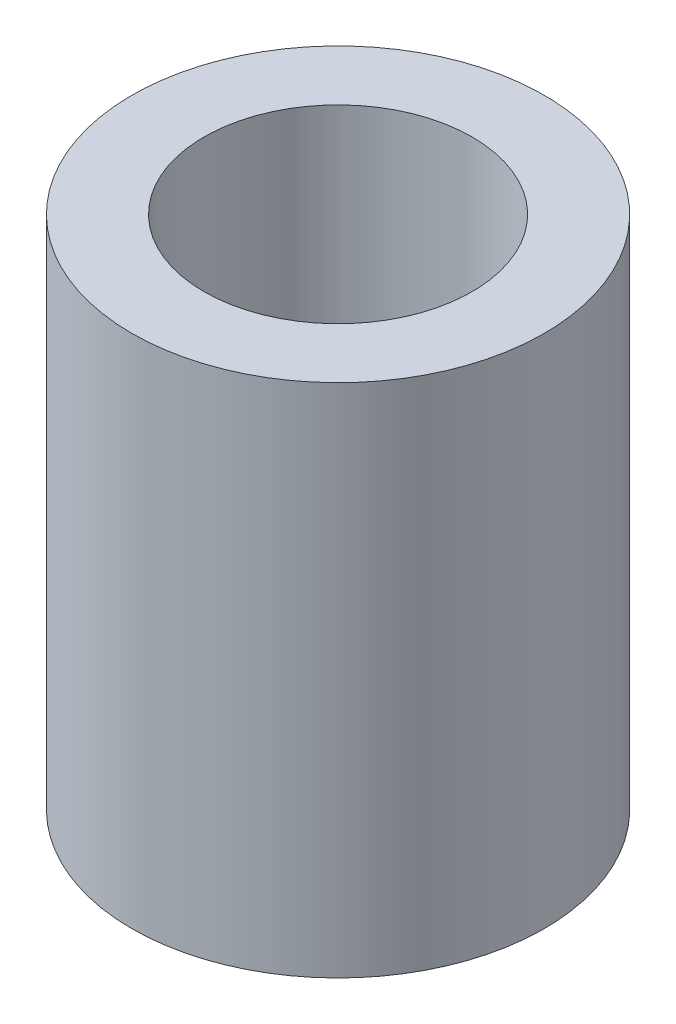
SolidWorks part; units mm, degrees
ref_plane "前视基准面" through (0, 0, 0) normal (0, 0, 1) x (1, 0, 0)
ref_plane "上视基准面" through (0, 0, 0) normal (0, 1, 0) x (1, 0, 0)
ref_plane "右视基准面" through (0, 0, 0) normal (1, 0, 0) x (0, 0, -1)
sketch "草图1" plane through (0, 0, 0) normal (0, 1, 0) x (1, 0, 0)
  circle A0 centre (0, 0) radius 2.6
  circle A1 centre (0, 0) radius 4
extrude "凸台-拉伸1" add sketch "草图1" along normal blind 10
